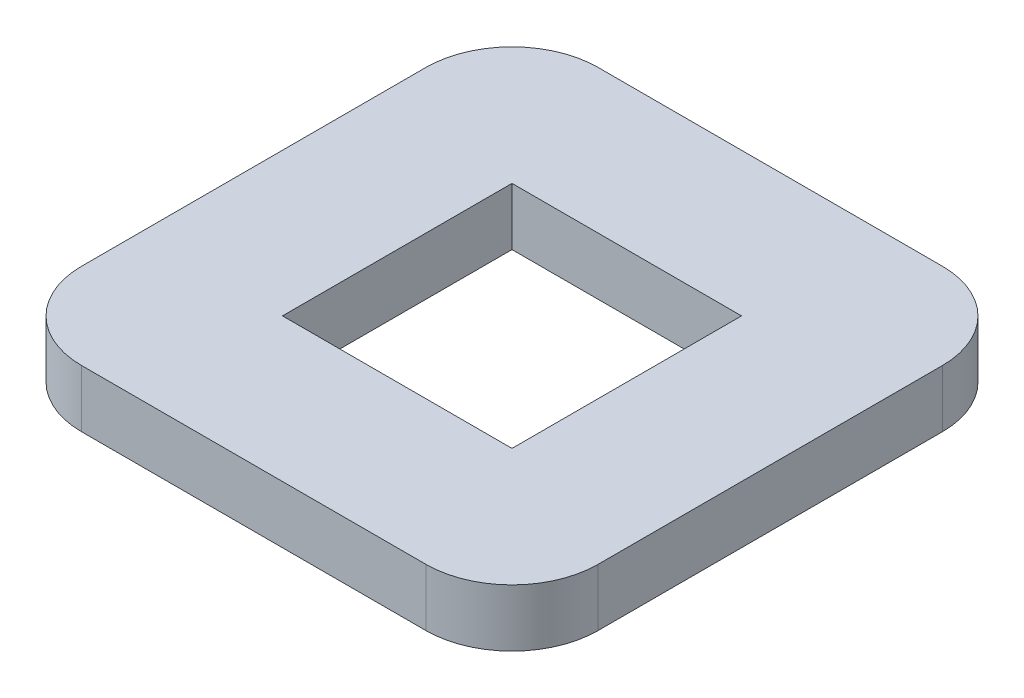
SolidWorks part; units mm, degrees
ref_plane "Front Plane" through (0, 0, 0) normal (0, 0, 1) x (1, 0, 0)
ref_plane "Top Plane" through (0, 0, 0) normal (0, 1, 0) x (1, 0, 0)
ref_plane "Right Plane" through (0, 0, 0) normal (1, 0, 0) x (0, 0, -1)
sketch "Sketch1" plane through (0, 0, 0) normal (0, 1, 0) x (1, 0, 0)
  line L0 (0, 9) -> (0, -9) construction
  line L5 (-9, 0) -> (9, 0) construction
  line L6 (-6, 9) -> (6, 9)
  line L7 (4, -4) -> (-4, -4)
  line L8 (4, -4) -> (4, 4)
  line L9 (4, 4) -> (-4, 4)
  line L10 (-4, -4) -> (-4, 4)
  line L11 (4, -4) -> (-4, 4) construction
  line L12 (4, 4) -> (-4, -4) construction
  line L13 (9, 6) -> (9, -6)
  line L14 (-9, 6) -> (-9, -6)
  line L15 (-6, -9) -> (6, -9)
  arc A0 (6, 9) -> (9, 6) centre (6, 6) cw
  arc A1 (-6, 9) -> (-9, 6) centre (-6, 6) ccw
  arc A2 (6, -9) -> (9, -6) centre (6, -6) ccw
  arc A3 (-6, -9) -> (-9, -6) centre (-6, -6) cw
  point P0 (0, 0)
  point P6 (0, 0)
  dimension "D1" = 18
  dimension "D2" = 8
  dimension "D3" = 6
extrude "Boss-Extrude1" add sketch "Sketch1" along normal blind 2
